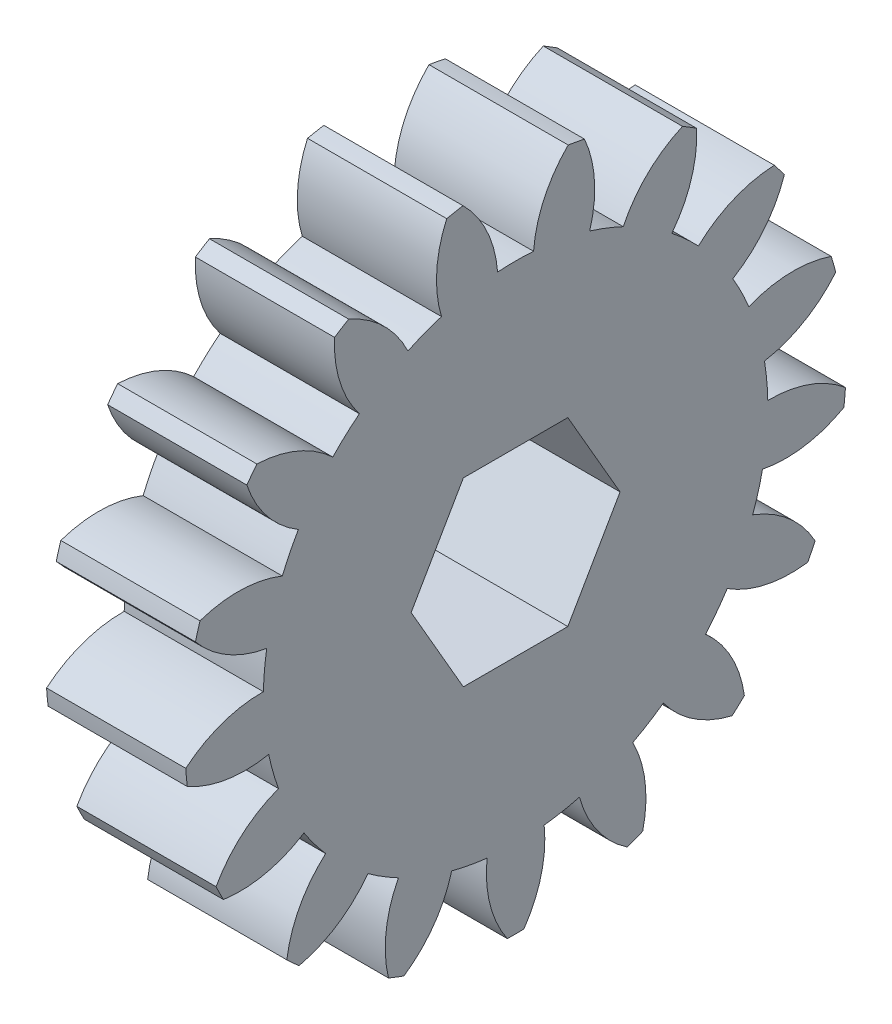
SolidWorks part; units mm, degrees
ref_plane "Plane1" through (0, 0, 0) normal (0, 0, 1) x (1, 0, 0)
ref_plane "Plane2" through (0, 0, 0) normal (0, 1, 0) x (1, 0, 0)
ref_plane "Plane3" through (0, 0, 0) normal (1, 0, 0) x (0, 0, -1)
sketch "HoldingSke" plane through (0, 0, 0) normal (0, 1, 0) x (1, 0, 0)
  line L0 (0, 0) -> (0.9563, -0.2924)
  line L1 (-15, 0) -> (100, 0) construction
  line L2 (0, 0) -> (-2.1039, 2.3779)
  line L3 (0, 0) -> (-11.863, 4.5341)
  line L4 (0, 0) -> (8.2586, 2.5249)
  line L5 (0, 0) -> (-46.8476, -17.4728)
  line L6 (0, 0) -> (-3.3159, -2.2372)
  line L7 (-2.1039, 2.3779) -> (8.6586, 51.2059)
  line L8 (-76.2, 54.61) -> (-76.1, 54.61)
  line L9 (-71.009, 38.7566) -> (-53.1078, 45.2721)
  line L10 (-76.2, 71.12) -> (104.1128, 71.12)
  line L11 (0, 0) -> (-4, 0)
  line L12 (-76.2, 101.6) -> (-76.162, 101.6)
  line L13 (24.9733, 27.94) -> (52.9518, 28.4284)
  line L14 (24.9733, 27.94) -> (24.9743, 27.94)
  line L15 (24.9733, 27.94) -> (100.4006, 29.5858)
  line L16 (-63.627, -1) -> (-12.827, -1)
  circle A0 centre (0, 0) radius 0.4
  circle A1 centre (0, 0) radius 7.249
  circle A2 centre (0, 0) radius 37.5
  circle A3 centre (0, 0) radius 0.4
  dimension "MHD" = 14.498
  dimension "Hub_dia" = 75
  dimension "Bore" = 0.8
  dimension "MBD" = 0.8
  dimension "Num_teeth" = 17
  dimension "Pitch" = 1
  dimension "Overall_len" = 50
  dimension "Show_teeth" = 17
  dimension "Thickness" = 4
  dimension "OAL" = 50.0001
  dimension "T_dim" = 0.1
  dimension "Ap" = 20
  dimension "H" = 19.05
  dimension "Pitch_radius" = 180.3128
  dimension "Width" = 4
  dimension "Backlash" = 0.038
  dimension "Addendum_fac" = 1
  dimension "Dedendum_fac" = 1.25
  dimension "Clearance_fac" = 0.25
  dimension "Dedendum_add" = 0.001
  dimension "Module" = 1
sketch "BasProSke" plane through (0, 0, 0) normal (0, 1, 0) x (1, 0, 0)
  line L0 (-10, 0) -> (60, 0) construction
  line L1 (0, 0) -> (0, 9.5)
  line L2 (0, 0) -> (4, 0)
  line L3 (4, 0) -> (4, 9.5)
  line L4 (4, 9.5) -> (0, 9.5)
  dimension "Thickness" = 4
  dimension "Diameter" = 19
revolve "Base-Revolve" add sketch "BasProSke" angle 360 about L0
sketch "TooCutSke" plane through (0, 0, 0) normal (1, 0, 0) x (0, 0, -1)
  line L1 (0, 0) -> (0, 107) construction
  line L2 (0, 0) -> (-0.8507, 8.4573) construction
  line L3 (0, 0) -> (-3.1126, 16.6509) construction
  line L4 (-0.8507, 8.4573) -> (-1.5563, 8.3254) construction
  arc A0 (0.5169, 7.2306) -> (-0.5169, 7.2306) centre (0, 0) ccw
  arc A1 (1.5331, 9.4012) -> (-1.5331, 9.4012) centre (0, 0) ccw
  circle A2 centre (0, 0) radius 8.5 construction
  circle A3 centre (0, 0) radius 7.9874 construction
  arc A4 (-0.5169, 7.2306) -> (-1.5331, 9.4012) centre (-3.9066, 6.9668) ccw
  arc A5 (1.5331, 9.4012) -> (0.5169, 7.2306) centre (3.9066, 6.9668) ccw
  dimension "Root_dia" = 14.498
  dimension "Overcut_dia" = 19.0508
  dimension "Pitch_dia" = 17
  dimension "Base_dia" = 15.9748
  dimension "Flank_rad" = 3.4
  dimension "Half_ang" = 10.588
  dimension "Half_CT" = 0.7178
extrude "ToothCut" cut sketch "TooCutSke" along normal through all
fillet "Breaks" [suppressed] radius 0.02
fillet "RootFillets" [suppressed] radius 0.251
pattern_circular "TeethCuts" count 17 every 21.176 about axis through (-10, 0, 0) along (1, 0, 0) of "ToothCut", "RootFillets", "Breaks"
sketch "HubNeaOneSke" plane through (0, 0, 0) normal (-1, 0, 0) x (0, 0, 1)
  circle A0 centre (0, 0) radius 7.249
  dimension "Diameter" = 14.498
extrude "HubNearOne" [suppressed] add sketch "HubNeaOneSke" along normal blind 46.0001
sketch "HubNeaBotSke" plane through (0, 0, 0) normal (-1, 0, 0) x (0, 0, 1)
  circle A0 centre (0, 0) radius 7.249
  dimension "Diameter" = 14.498
extrude "HubNearBoth" [suppressed] add sketch "HubNeaBotSke" along normal blind 23
ref_plane "FarPln" through (4, 0, 0) normal (1, 0, 0) x (0, 0, -1)
sketch "HubFarSke" plane through (4, 0, 0) normal (1, 0, 0) x (0, 0, -1)
  circle A0 centre (0, 0) radius 7.249
  dimension "Diameter" = 14.498
extrude "HubFar" [suppressed] add sketch "HubFarSke" along normal blind 23
sketch "BorSke" plane through (0, 0, 0) normal (1, 0, 0) x (0, 0, -1)
  circle A0 centre (0, 0) radius 0.4
  dimension "Diameter" = 0.8
extrude "Bore" cut sketch "BorSke" along normal mid plane 100.0001
sketch "KeySke" plane through (0, 0, 0) normal (1, 0, 0) x (0, 0, -1)
  line L0 (-0.05, 0) -> (-0.05, 0.5)
  line L1 (-0.05, 0.5) -> (0.05, 0.5)
  line L2 (0.05, 0.5) -> (0.05, 0)
  line L3 (0, 0) -> (0, 34) construction
  line L4 (-0.05, 0) -> (0.05, 0)
  dimension "Offset" = 0.5
  dimension "Width" = 0.1
extrude "Keyway" [suppressed] cut sketch "KeySke" along normal mid plane 100.0001
pattern_circular "Keyway2" [suppressed] count 2 every 90 about axis through (-10, 0, 0) along (1, 0, 0)
sketch "Sketch1" plane through (4, 0, 0) normal (1, 0, 0) x (0, 0, -1)
  line L1 (3.0022, 0) -> (1.5011, 2.6)
  line L2 (1.5011, 2.6) -> (-1.5011, 2.6)
  line L3 (-1.5011, 2.6) -> (-3.0022, 0)
  line L4 (-3.0022, 0) -> (-1.5011, -2.6)
  line L5 (-1.5011, -2.6) -> (1.5011, -2.6)
  line L6 (1.5011, -2.6) -> (3.0022, 0)
  circle A0 centre (0, 0) radius 2.6 construction
  dimension "D1" = 5.2
extrude "Cut-Extrude1" cut sketch "Sketch1" against normal through all
equation "' \"Module@HoldingSke\" = 6.35"
equation "' \"Num_teeth@HoldingSke\" = 12"
equation "' \"Ap@HoldingSke\" =  20"
equation "' \"Ap@HoldingSke\" = 20"
equation "' \"Width@HoldingSke\" = 0.5 * 25.4"
equation "' \"Hub_dia@HoldingSke\"= 1 * 25.4"
equation "' \"Hub_dia@HoldingSke\" = 1 * 25.4"
equation "' \"Overall_len@HoldingSke\" = 1.0 * 25.4"
equation "' \"Bore@HoldingSke\" = 0.75 * 25.4"
equation "' \"T_dim@HoldingSke\" = 0.1 * 25.4"
equation "' \"Width@KeySke\" = 0.25 * 25.4"
equation "' \"Show_teeth@HoldingSke\" = 13"
equation "' \"Backlash@HoldingSke\" = 0.009 * 25.4"
equation "' \"Addendum_fac@HoldingSke\" = 1.0"
equation "' \"Dedendum_fac@HoldingSke\" = 1.25"
equation "' \"Dedendum_add@HoldingSke\" = 0.00005 * 25.4"
equation "' \"Clearance_fac@HoldingSke\" = 0.25"
equation "\"Pitch@HoldingSke\" = 1 / \"Module@HoldingSke\""
equation "\"Overcut_dia@TooCutSke\" = (\"Num_teeth@HoldingSke\" + 2 * \"Addendum_fac@HoldingSke\") / \"Pitch@HoldingSke\" + 0.002 * 25.4"
equation "\"Pitch_dia@TooCutSke\" = \"Num_teeth@HoldingSke\" / \"Pitch@HoldingSke\""
equation "\"Base_dia@TooCutSke\" = \"Num_teeth@HoldingSke\" / \"Pitch@HoldingSke\" * cos((\"Ap@HoldingSke\"  * 3.14159265 / 180))"
equation "\"Root_dia@TooCutSke\" = (\"Num_teeth@HoldingSke\" + 2) / \"Pitch@HoldingSke\" - 2 * (\"Addendum_fac@HoldingSke\" + \"Dedendum_fac@HoldingSke\") / \"Pitch@HoldingSke\" - \"Dedendum_add@HoldingSke\" * 2"
equation "\"Half_ang@TooCutSke\" = 180 / \"Num_teeth@HoldingSke\""
equation "\"Half_CT@TooCutSke\" = \"Num_teeth@HoldingSke\" / \"Pitch@HoldingSke\" * sin((3.14159265 / 2 / \"Num_teeth@HoldingSke\")) / 2 - 7 * \"Backlash@HoldingSke\" / 4"
equation "\"Flank_rad@TooCutSke\" = \"Num_teeth@HoldingSke\" / \"Pitch@HoldingSke\" / 5"
equation "\"Radius@RootFillets\" = \"Clearance_fac@HoldingSke\" / \"Pitch@HoldingSke\" + \"Dedendum_add@HoldingSke\""
equation "\"Break_rad@Breaks\" = 0.02 / \"Pitch@HoldingSke\""
equation "\"Thickness@HoldingSke\" = \"Width@HoldingSke\""
equation "\"OAL@HoldingSke\" = \"Thickness@HoldingSke\""
equation "\"MHD@HoldingSke\" = (\"Num_teeth@HoldingSke\" + 2) / \"Pitch@HoldingSke\" - 2 * (\"Addendum_fac@HoldingSke\" + \"Dedendum_fac@HoldingSke\")  / \"Pitch@HoldingSke\" - \"Dedendum_add@HoldingSke\" * 2"
equation "\"MBD@HoldingSke\" = (\"Num_teeth@HoldingSke\" + 2) / \"Pitch@HoldingSke\" - 2 * (\"Addendum_fac@HoldingSke\" + \"Dedendum_fac@HoldingSke\")  / \"Pitch@HoldingSke\" - \"Dedendum_add@HoldingSke\" * 2 - 0.002 * 25.4"
equation "\"MHD@HoldingSke\" = ((sgn( \"MHD@HoldingSke\" - \"Hub_dia@HoldingSke\" )-1)*( \"MHD@HoldingSke\" - \"Hub_dia@HoldingSke\" ))/-2+ \"Hub_dia@HoldingSke\""
equation "\"MBD@HoldingSke\" = ((sgn( \"MBD@HoldingSke\" - \"Bore@HoldingSke\" )-1)*( \"MBD@HoldingSke\" - \"Bore@HoldingSke\" ))/-2+ \"Bore@HoldingSke\""
equation "\"OAL@HoldingSke\" = ((sgn( \"OAL@HoldingSke\" - \"Overall_len@HoldingSke\" )+1)*( \"OAL@HoldingSke\" - \"Overall_len@HoldingSke\" ))/2 + \"Overall_len@HoldingSke\" + 0.000002 * 25.4"
equation "\"Num_teeth@TeethCuts\" = int( \"Show_teeth@HoldingSke\" ) + 1"
equation "\"Num_teeth@TeethCuts\" = ((sgn( \"Num_teeth@TeethCuts\" - \"Num_teeth@HoldingSke\" )-1)*( \"Num_teeth@TeethCuts\" - \"Num_teeth@HoldingSke\" ))/-2+ \"Num_teeth@HoldingSke\""
equation "\"Num_teeth@TeethCuts\" = ((sgn( \"Num_teeth@TeethCuts\" - 2.0)+1)*( \"Num_teeth@TeethCuts\" - 2.0))/2 +2.0"
equation "\"Angle@TeethCuts\" = 360.0 / \"Num_teeth@HoldingSke\""
equation "\"Diameter@BasProSke\" = (\"Num_teeth@HoldingSke\" + 2 * \"Addendum_fac@HoldingSke\") / \"Pitch@HoldingSke\""
equation "\"Thickness@BasProSke\"  = \"Thickness@HoldingSke\""
equation "' \"Fillet_rad@BasProSke\" =  \"Thickness@HoldingSke\" * 0.05"
equation "' \"Fillet_rad@BasProSke\" = \"Thickness@HoldingSke\" * 0.05"
equation "\"MHD@HoldingSke\" = ((sgn( \"MHD@HoldingSke\" - \"Root_dia@TooCutSke\" )-1)*( \"MHD@HoldingSke\" - \"Root_dia@TooCutSke\" ))/-2+ \"Root_dia@TooCutSke\""
equation "\"Diameter@HubNeaOneSke\" = \"MHD@HoldingSke\""
equation "\"Length@HubNearOne\" = \"OAL@HoldingSke\" - \"Thickness@BasProSke\""
equation "\"Diameter@HubNeaBotSke\" = \"MHD@HoldingSke\""
equation "\"Length@HubNearBoth\" = ( \"OAL@HoldingSke\" - \"Thickness@BasProSke\" ) / 2.0"
equation "\"Thickness@FarPln\" = \"Thickness@BasProSke\""
equation "\"Diameter@HubFarSke\" = \"MHD@HoldingSke\""
equation "\"Length@HubFar\" = ( \"OAL@HoldingSke\" - \"Thickness@BasProSke\" ) / 2.0"
equation "\"Diameter@BorSke\" = \"MBD@HoldingSke\""
equation "\"D1@Bore\" = \"OAL@HoldingSke\" * 2.0"
equation "\"D1@Keyway\" = \"OAL@HoldingSke\" * 2.0"
equation "\"Offset@KeySke\" = \"T_dim@HoldingSke\" + \"MBD@HoldingSke\" / 2.0"
